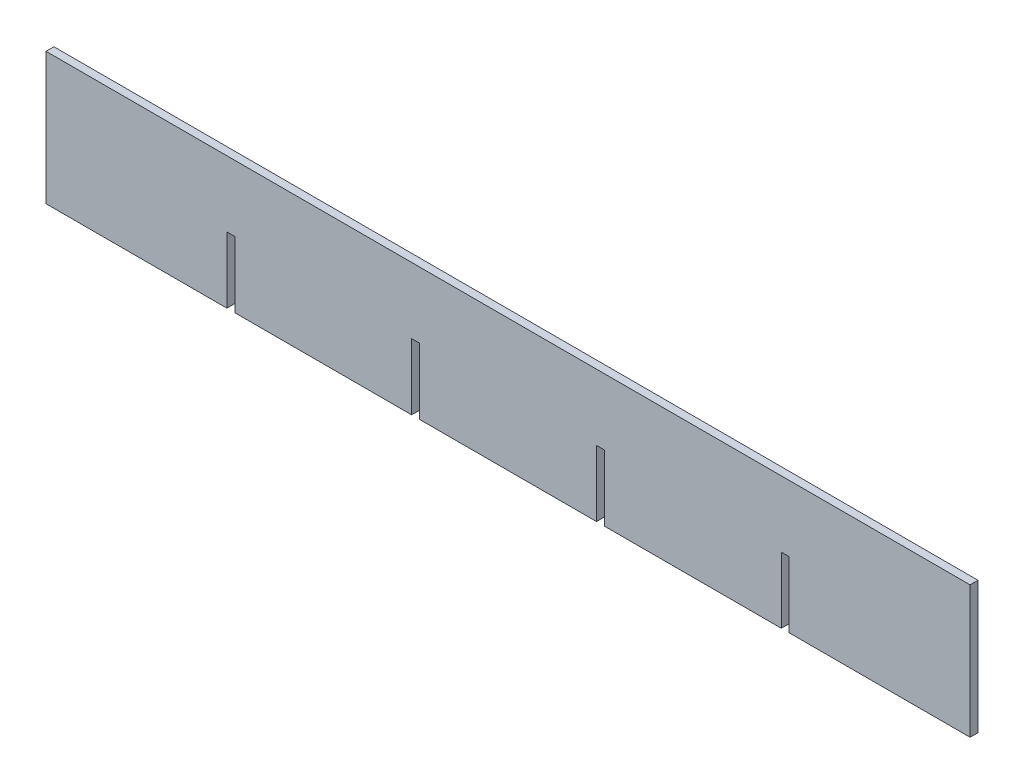
SolidWorks part; units mm, degrees
ref_plane "Front Plane" through (0, 0, 0) normal (0, 0, 1) x (1, 0, 0)
ref_plane "Top Plane" through (0, 0, 0) normal (0, 1, 0) x (1, 0, 0)
ref_plane "Right Plane" through (0, 0, 0) normal (1, 0, 0) x (0, 0, -1)
sketch "Sketch1" plane through (0, 0, 0) normal (0, 0, 1) x (1, 0, 0)
  line L1 (0, 0) -> (350, 0)
  line L2 (0, 0) -> (0, 50)
  line L3 (0, 50) -> (350, 50)
  line L4 (350, 0) -> (350, 50)
  line L5 (68.5, 0) -> (71.5, 0)
  line L6 (68.5, 0) -> (68.5, 25)
  line L7 (68.5, 25) -> (71.5, 25)
  line L8 (71.5, 0) -> (71.5, 25)
  line L9 (138.5, 0) -> (141.5, 0)
  line L10 (138.5, 0) -> (138.5, 25)
  line L11 (138.5, 25) -> (141.5, 25)
  line L12 (141.5, 0) -> (141.5, 25)
  line L13 (208.5, 0) -> (211.5, 0)
  line L14 (208.5, 0) -> (208.5, 25)
  line L15 (208.5, 25) -> (211.5, 25)
  line L16 (211.5, 0) -> (211.5, 25)
  line L17 (278.5, 0) -> (281.5, 0)
  line L18 (278.5, 0) -> (278.5, 25)
  line L19 (278.5, 25) -> (281.5, 25)
  line L20 (281.5, 0) -> (281.5, 25)
  point P25 (70, 25)
  point P26 (140, 25)
  point P27 (210, 25)
  point P28 (280, 25)
  dimension "D1" = 50
  dimension "D2" = 350
  dimension "D3" = 70
  dimension "D4" = 25
  dimension "D5" = 3
  dimension "D6" = 3
  dimension "D7" = 3
  dimension "D8" = 3
  dimension "D10" = 25
  dimension "D11" = 25
  dimension "D12" = 25
  dimension "D14" = 140
  dimension "D15" = 210
  dimension "D16" = 280
extrude "Boss-Extrude3" add sketch "Sketch1" along normal blind 3 contours L20 L1 L4 L3 L2 L6 L7 L8 L10 L11 L12 L14 L15 L16 L18 L19
